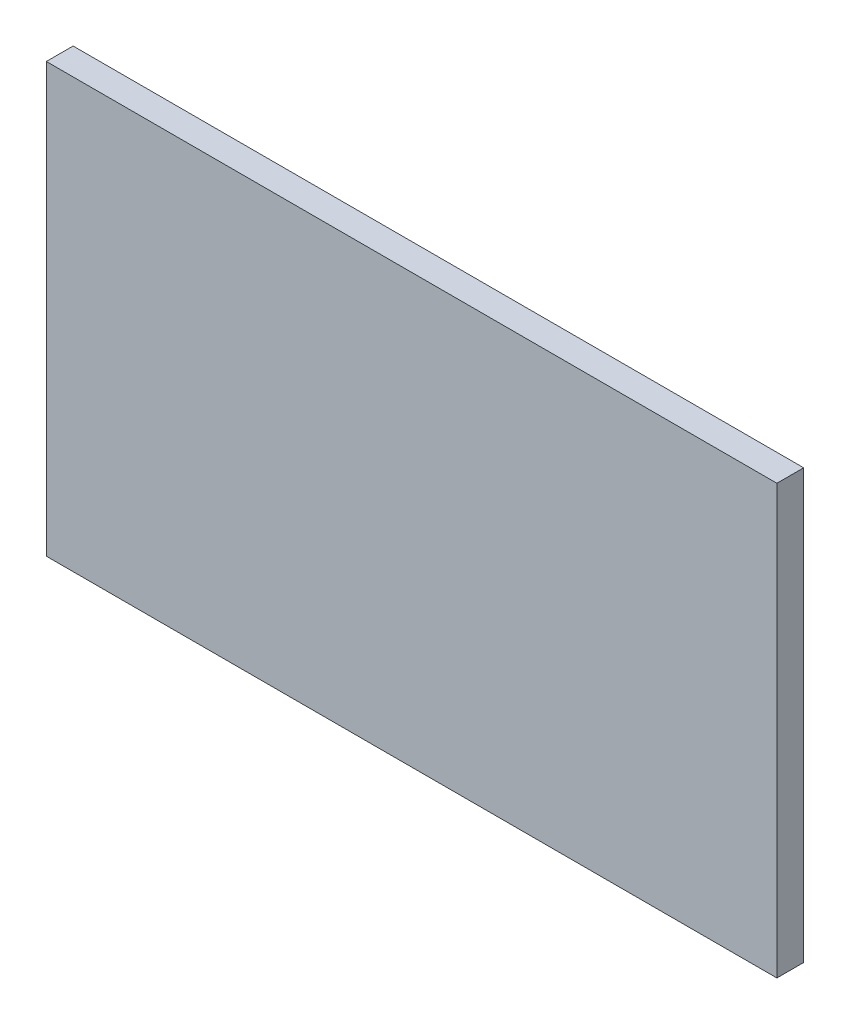
SolidWorks part; units mm, degrees
ref_plane "Front Plane" through (0, 0, 0) normal (0, 0, 1) x (1, 0, 0)
ref_plane "Top Plane" through (0, 0, 0) normal (0, 1, 0) x (1, 0, 0)
ref_plane "Right Plane" through (0, 0, 0) normal (1, 0, 0) x (0, 0, -1)
sketch "Sketch1" plane through (0, 0, 0) normal (0, 0, 1) x (1, 0, 0)
  line L1 (0, 0) -> (682, 0)
  line L2 (0, 0) -> (0, 400)
  line L3 (0, 400) -> (682, 400)
  line L4 (682, 0) -> (682, 400)
  dimension "D1" = 682
  dimension "D2" = 400
extrude "Boss-Extrude1" add sketch "Sketch1" along normal blind 25
